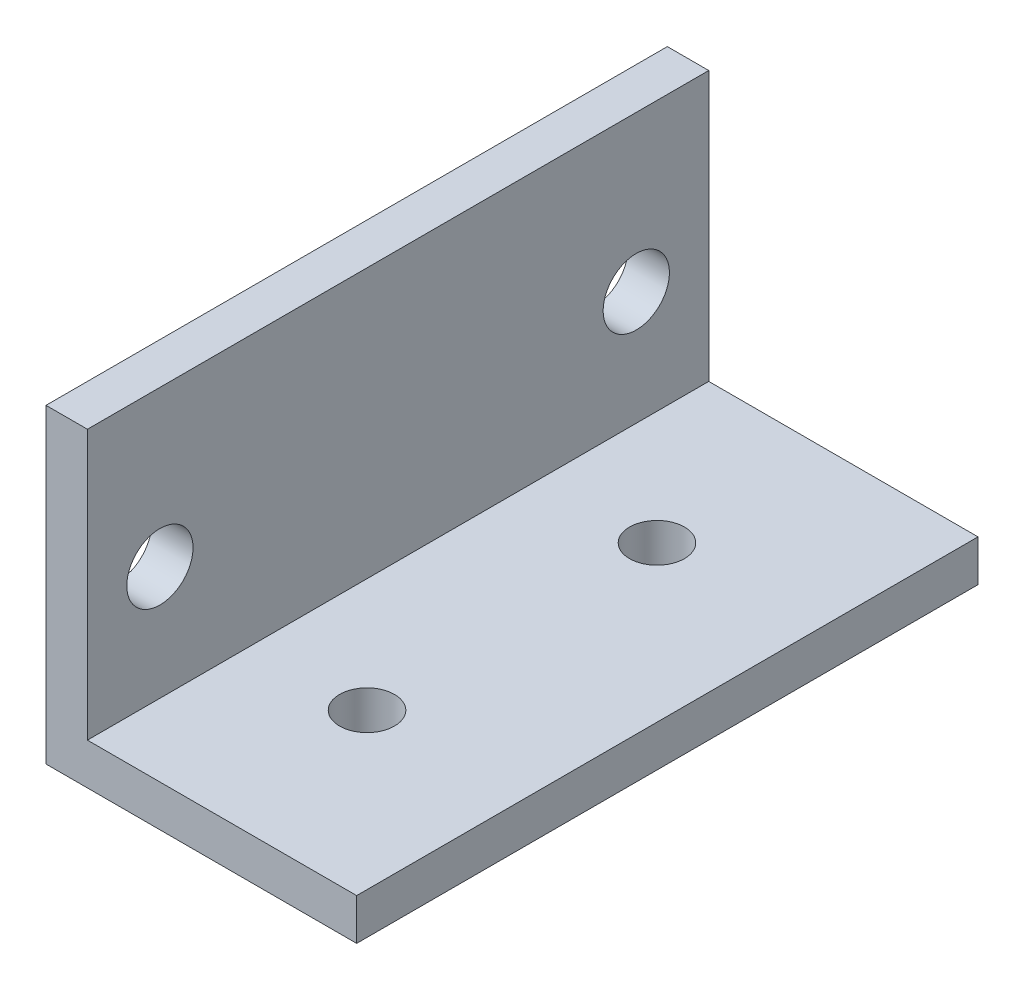
SolidWorks part; units mm, degrees
ref_plane "Front Plane" through (0, 0, 0) normal (0, 0, 1) x (1, 0, 0)
ref_plane "Top Plane" through (0, 0, 0) normal (0, 1, 0) x (1, 0, 0)
ref_plane "Right Plane" through (0, 0, 0) normal (1, 0, 0) x (0, 0, -1)
sketch "Sketch1" plane through (0, 0, 0) normal (0, 0, 1) x (1, 0, 0)
  line L1 (0, 30) -> (0, 0)
  line L2 (0, -55) -> (0, 55) construction
  line L3 (0, 0) -> (30, 0)
  line L4 (55, 0) -> (-55, 0) construction
  line L6 (30, 0) -> (30, 4)
  line L7 (30, 4) -> (4, 4)
  line L8 (4, 4) -> (4, 30)
  line L9 (4, 30) -> (0, 30)
  dimension "D1" = 30
  dimension "D2" = 30
  dimension "D3" = 4
  dimension "D4" = 4
extrude "Boss-Extrude1" add sketch "Sketch1" along normal blind 60
hole_wizard "M6 Clearance Hole1" positions "Sketch3" profile "Sketch2" hole size "M6" standard "ISO"
sketch "Sketch3" plane through (0, 0, 0) normal (-1, 0, 0) x (0, 0, 1)
  line L0 (16.5, 0) -> (-16.5, 0) construction
  line L1 (0, -16.5) -> (0, 16.5) construction
  point P0 (7, 15)
  point P2 (53, 15)
  dimension "D1" = 15
  dimension "D2" = 15
  dimension "D3" = 46
  dimension "D4" = 7
sketch "Sketch2" plane through (0, 15, 7) normal (0, 1, 0) x (0, 0, 1)
  line L0 (0, 0) -> (0, 9.9228)
  line L1 (0, 9.9228) -> (3.2, 8)
  line L2 (3.2, 8) -> (3.2, 0)
  line L5 (3.2, 0) -> (0, 0)
  line L10 (0, 9.9228) -> (-3.2, 8) construction
  line L11 (0, -6.35) -> (0, 107.95) construction
  dimension "Hole Dia." = 6.4
  dimension "Hole Depth" = 8
  dimension "Drill Angle" = 118
hole_wizard "M5 Clearance Hole1" positions "Sketch5" profile "Sketch4" hole size "M5" standard "ISO"
sketch "Sketch5" plane through (0, 0, 0) normal (0, -1, 0) x (-1, 0, 0)
  line L0 (0, 16.5) -> (0, -16.5) construction
  line L1 (-16.5, 0) -> (16.5, 0) construction
  line L2 (0, -60) -> (-30, -60) construction
  point P0 (-15, -16)
  point P2 (-15, -44)
  dimension "D1" = 15
  dimension "D2" = 15
  dimension "D3" = 16
  dimension "D4" = 16
sketch "Sketch4" plane through (15, 0, 16) normal (1, 0, 0) x (0, 0, -1)
  line L0 (0, 0) -> (0, 9.5923)
  line L1 (0, 9.5923) -> (2.65, 8)
  line L2 (2.65, 8) -> (2.65, 0)
  line L5 (2.65, 0) -> (0, 0)
  line L10 (0, 9.5923) -> (-2.65, 8) construction
  line L11 (0, -6.35) -> (0, 107.95) construction
  dimension "Hole Dia." = 5.3
  dimension "Hole Depth" = 8
  dimension "Drill Angle" = 118
